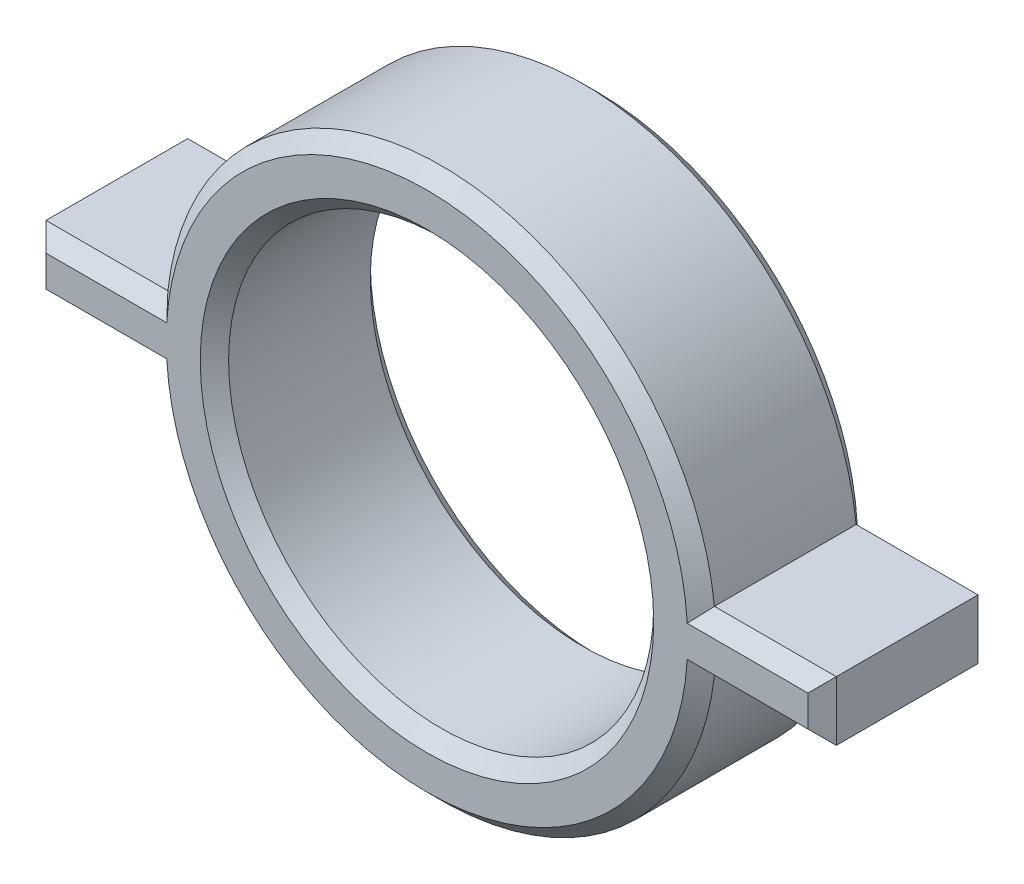
SolidWorks part; units mm, degrees
material "PLA"
ref_plane "Front Plane" through (0, 0, 0) normal (0, 0, 1) x (1, 0, 0)
ref_plane "Top Plane" through (0, 0, 0) normal (0, 1, 0) x (1, 0, 0)
ref_plane "Right Plane" through (0, 0, 0) normal (1, 0, 0) x (0, 0, -1)
sketch "Sketch1" plane through (0, 0, 0) normal (0, 0, 1) x (1, 0, 0)
  line L6 (9.643, -1.05) -> (13.943, -1.05)
  line L7 (13.943, -1.05) -> (13.943, 1.05)
  line L8 (13.943, 1.05) -> (9.643, 1.05)
  line L9 (-13.943, 1.05) -> (-13.943, -1.05)
  line L10 (-9.643, 1.05) -> (-13.943, 1.05)
  line L11 (-13.943, -1.05) -> (-9.643, -1.05)
  line L12 (0, 0) -> (16.0081, 0) construction
  line L13 (0, 0) -> (0, -4.3408) construction
  arc A4 (9.643, 1.05) -> (-9.643, 1.05) centre (0, 0) ccw
  arc A5 (-9.643, -1.05) -> (9.643, -1.05) centre (0, 0) ccw
  circle A6 centre (0, 0) radius 7.5
  dimension "D1" = 9.7
  dimension "D4" = 15
  dimension "D2" = 2.1
  dimension "D3" = 4.3
extrude "Boss-Extrude1" add sketch "Sketch1" along normal blind 6
chamfer "Chamfer1" distance 0.5 angle 45 18 edges at (7.5, 0, 0) (-13.943, 0, 0) (-11.793, -1.05, 0) (0, -9.7, 0) (11.793, -1.05, 0) (13.943, 0, 0) (11.793, 1.05, 0) (0, 9.7, 0) (-11.793, 1.05, 0) (7.5, 0, 6) (0, 9.7, 6) (11.793, 1.05, 6) (13.943, 0, 6) (11.793, -1.05, 6) (0, -9.7, 6) (-11.793, -1.05, 6) (-13.943, 0, 6) (-11.793, 1.05, 6)
